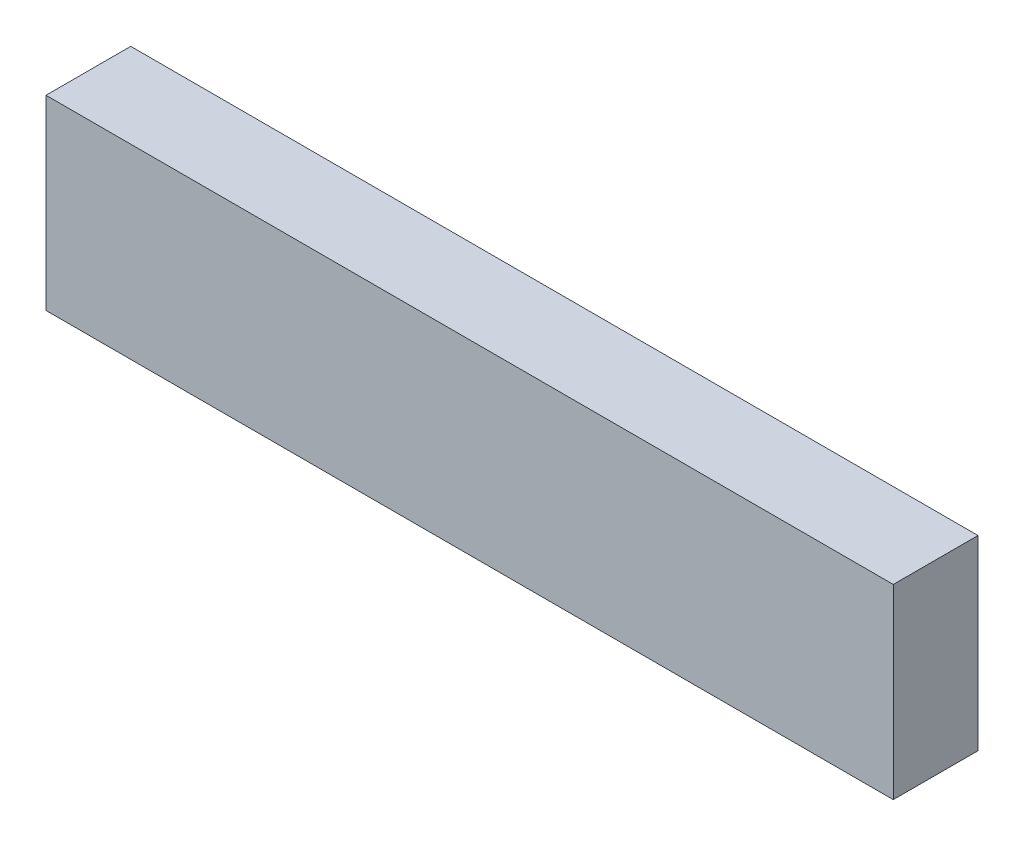
SolidWorks part; units mm, degrees
ref_plane "前视基准面" through (0, 0, 0) normal (0, 0, 1) x (1, 0, 0)
ref_plane "上视基准面" through (0, 0, 0) normal (0, 1, 0) x (1, 0, 0)
ref_plane "右视基准面" through (0, 0, 0) normal (1, 0, 0) x (0, 0, -1)
sketch "edrawing1" plane through (0, 0, 0) normal (0, 0, 1) x (1, 0, 0)
  line L1 (-50, 11) -> (0, 11)
  line L2 (-50, 11) -> (-50, 0)
  line L3 (-50, 0) -> (0, 0)
  line L4 (0, 11) -> (0, 0)
  dimension "DS_D1" = 50
  dimension "DS_D2" = 11
extrude "extrude1" add sketch "edrawing1" along normal blind 5
